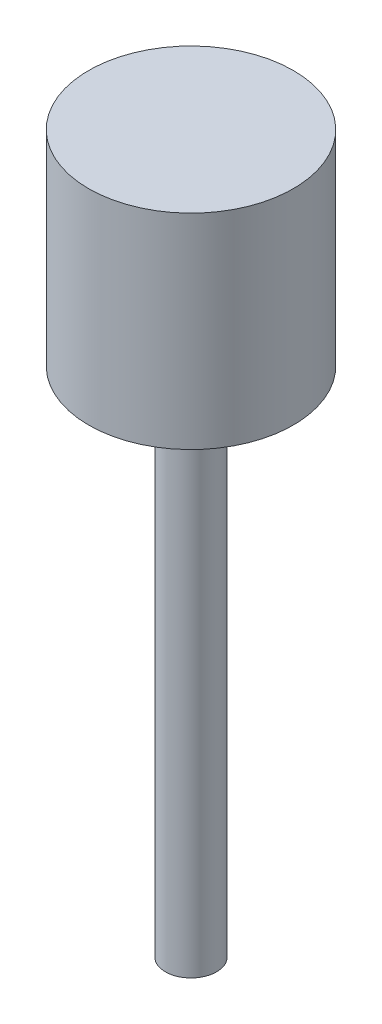
SolidWorks part; units mm, degrees
ref_plane "Front" through (0, 0, 0) normal (0, 0, 1) x (1, 0, 0)
ref_plane "Top" through (0, 0, 0) normal (0, 1, 0) x (1, 0, 0)
ref_plane "Right" through (0, 0, 0) normal (1, 0, 0) x (0, 0, -1)
sketch "Esboço1" plane through (0, 0, 0) normal (0, 0, 1) x (1, 0, 0)
  line L0 (0, 0) -> (0, 70)
  line L1 (0, 70) -> (10, 70)
  line L2 (10, 70) -> (10, 50)
  line L3 (10, 50) -> (2.5, 50)
  line L4 (2.5, 50) -> (2.5, 0)
  line L5 (2.5, 0) -> (0, 0)
  line L6 (0, 0) -> (0, 108.0231) construction
  dimension "D1" = 20
  dimension "D2" = 20
  dimension "D3" = 5
  dimension "D4" = 50
revolve "Revolução1" add sketch "Esboço1" angle 360 about L6
